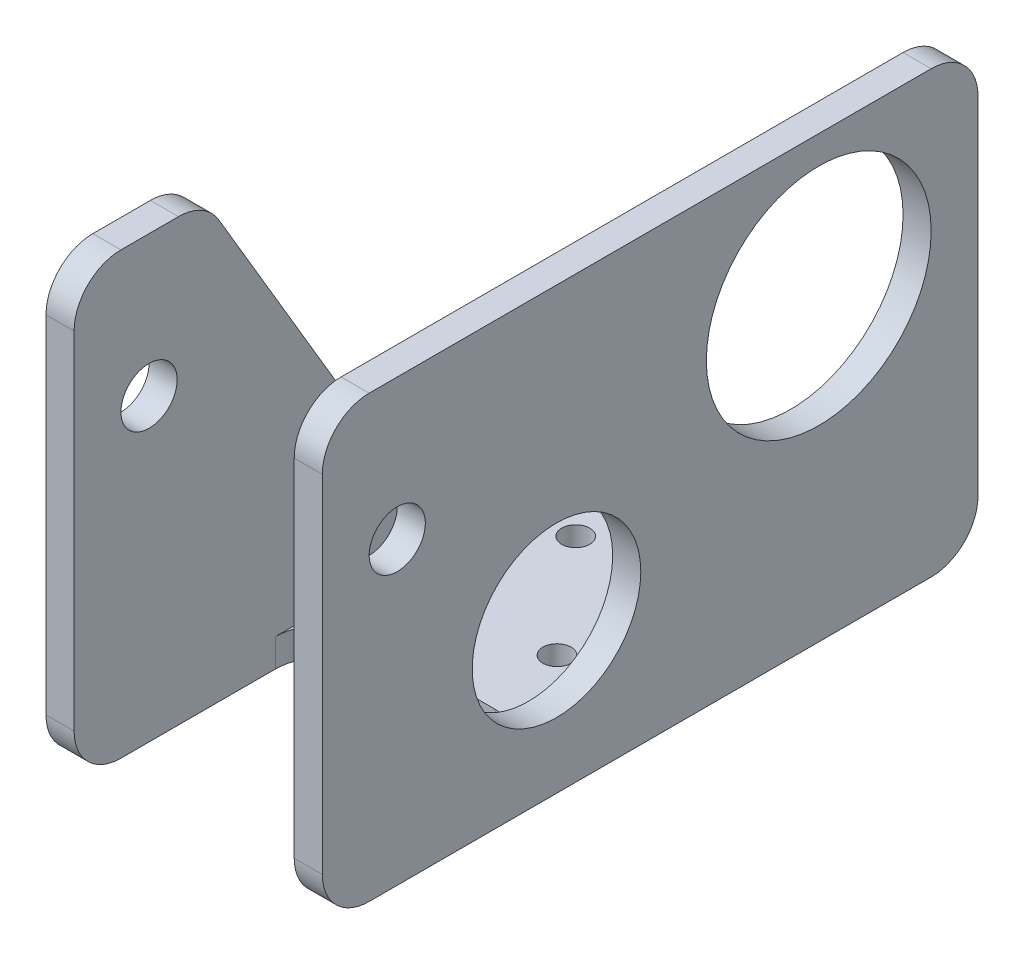
SolidWorks part; units mm, degrees
material "6061 合金"
ref_plane "前视基准面" through (0, 0, 0) normal (0, 0, 1) x (1, 0, 0)
ref_plane "上视基准面" through (0, 0, 0) normal (0, 1, 0) x (1, 0, 0)
ref_plane "右视基准面" through (0, 0, 0) normal (1, 0, 0) x (0, 0, -1)
sketch "草图1" plane through (0, 0, 0) normal (0, 0, 1) x (1, 0, 0)
  line L1 (0, 0) -> (29.5, 0)
  line L2 (0, 0) -> (0, 47)
  line L3 (0, 47) -> (29.5, 47)
  line L4 (29.5, 0) -> (29.5, 47)
  dimension "D1" = 47
  dimension "D2" = 29.5
extrude "凸台-拉伸1" add sketch "草图1" along normal blind 70
sketch "草图2" plane through (0, 0, 70) normal (0, 0, 1) x (1, 0, 0)
  line L0 (29.5, 47) -> (0, 47) construction
  line L1 (3, 3) -> (26.5, 3)
  line L2 (3, 3) -> (3, 47)
  line L3 (3, 47) -> (26.5, 47)
  line L4 (26.5, 3) -> (26.5, 47)
  line L5 (0, 0) -> (29.5, 0) construction
  line L6 (29.5, 0) -> (29.5, 47) construction
  line L7 (0, 47) -> (0, 0) construction
  dimension "D1" = 3
  dimension "D2" = 3
  dimension "D3" = 3
extrude "切除-拉伸1" cut sketch "草图2" against normal blind 70
sketch "草图5" plane through (29.5, 0, 0) normal (1, 0, 0) x (0, 0, -1)
  line L1 (-70, 0) -> (0, 0) construction
  line L2 (0, 0) -> (0, 47) construction
  circle A0 centre (-17, 32) radius 12
  circle A1 centre (-62, 32) radius 3
  dimension "D1" = 24
  dimension "D2" = 6
  dimension "D3" = 45
  dimension "D4" = 17
  dimension "D5" = 32
extrude "切除-拉伸4" cut sketch "草图5" against normal blind 70
sketch "草图10" plane through (29.5, 0, 0) normal (1, 0, 0) x (0, 0, -1)
  line L0 (-70, 0) -> (0, 0) construction
  line L1 (0, 0) -> (0, 47) construction
  circle A6 centre (-45, 16) radius 9
  dimension "D1" = 16
  dimension "D2" = 45
  dimension "D3" = 18
extrude "切除-拉伸8" cut sketch "草图10" against normal blind 17
sketch "草图11" plane through (0, 0, 0) normal (0, -1, 0) x (1, 0, 0)
  line L1 (0, 70) -> (0, 0) construction
  line L2 (29.5, 70) -> (29.5, 0) construction
  line L4 (3, 70) -> (26.5, 70)
  line L5 (3, 70) -> (3, 43.5)
  line L6 (3, 43.5) -> (26.5, 43.5)
  line L7 (26.5, 70) -> (26.5, 43.5)
  line L16 (0, 70) -> (29.5, 70) construction
  line L17 (26.5, 0) -> (26.5, 15)
  line L18 (0, 0) -> (29.5, 0) construction
  line L19 (26.5, 15) -> (3, 15)
  line L20 (3, 15) -> (3, 0)
  line L21 (3, 0) -> (26.5, 0)
  dimension "D1" = 28.5
  dimension "D2" = 15
  dimension "D7" = 3
  dimension "D8" = 3
extrude "切除-拉伸9" cut sketch "草图11" against normal blind 10
fillet "圆角2" radius 5 6 edges at (3, 1.5, 43.5) (26.5, 1.5, 43.5) (1.5, 0, 70) (1.5, 0, 0) (28, 0, 0) (28, 0, 70)
sketch "草图13" plane through (3, 0, 0) normal (1, 0, 0) x (0, 0, -1)
  line L0 (-15, 0) -> (-15, 3)
  line L2 (0, 47) -> (-70, 47) construction
  line L3 (-56, 47) -> (0, 47)
  line L4 (0, 47) -> (0, 0)
  line L5 (0, 0) -> (-15, 0)
  line L6 (-15, 0) -> (-5, 0) construction
  line L7 (-70, 47) -> (-70, 5) construction
  line L8 (-15, 3) -> (-48.5, 3) construction
  line L9 (-15, 3) -> (-30, 3)
  line L10 (-30, 3) -> (-56, 47)
  line L11 (-15, 3) -> (-15, 0) construction
  dimension "D1" = 14
  dimension "D2" = 15
extrude "切除-拉伸11" cut sketch "草图13" against normal blind 10
fillet "圆角3" radius 5 7 edges at (1.5, 47, 70) (28, 47, 70) (28, 47, 0) (1.5, 3, 30) (0, 1.5, 15) (26.5, 1.5, 15) (1.5, 47, 56)
sketch "草图14" plane through (0, 0, 0) normal (0, -1, 0) x (1, 0, 0)
  line L0 (0, 65) -> (0, 20) construction
  line L1 (9.75, 35.2) -> (19.75, 35.2) construction
  line L2 (9.75, 35.2) -> (9.75, 23.2) construction
  line L3 (9.75, 23.2) -> (19.75, 23.2) construction
  line L4 (19.75, 35.2) -> (19.75, 23.2) construction
  line L5 (8, 43.5) -> (21.5, 43.5) construction
  circle A0 centre (9.75, 35.2) radius 1.5
  circle A1 centre (9.75, 23.2) radius 1.5
  circle A2 centre (19.75, 23.2) radius 1.5
  circle A3 centre (19.75, 35.2) radius 1.5
  dimension "D5" = 3
  dimension "D6" = 3
  dimension "D7" = 3
  dimension "D8" = 3
  dimension "D1" = 10
  dimension "D2" = 9.75
  dimension "D3" = 8.3
  dimension "D4" = 12
extrude "切除-拉伸12" cut sketch "草图14" against normal blind 10
